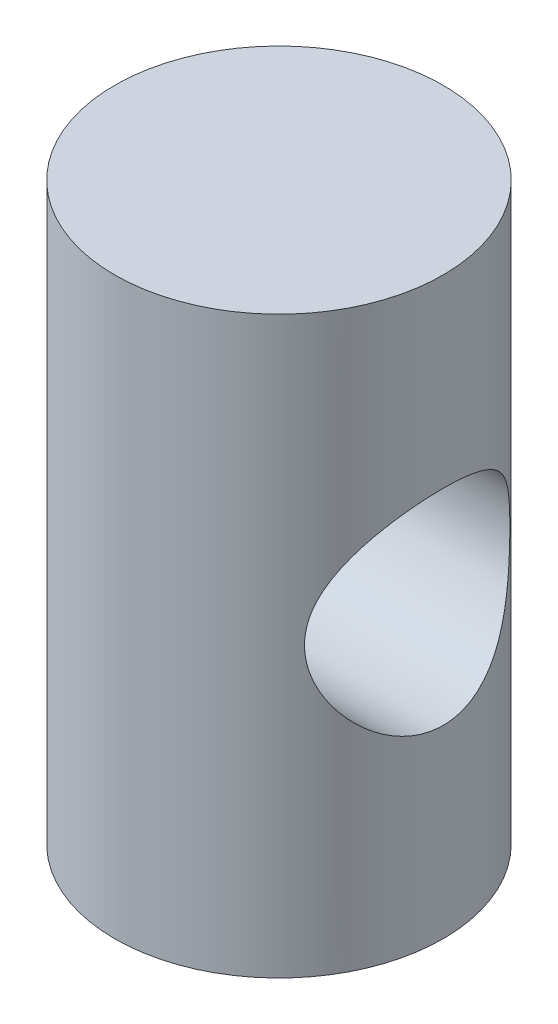
SolidWorks part; units mm, degrees
material "1023 Carbon Steel Sheet (SS)"
ref_plane "Front Plane" through (0, 0, 0) normal (0, 0, 1) x (1, 0, 0)
ref_plane "Top Plane" through (0, 0, 0) normal (0, 1, 0) x (1, 0, 0)
ref_plane "Right Plane" through (0, 0, 0) normal (1, 0, 0) x (0, 0, -1)
sketch "Sketch1" plane through (0, 0, 0) normal (0, 1, 0) x (1, 0, 0)
  circle A0 centre (0, 0) radius 4
  dimension "D1" = 8
extrude "Boss-Extrude1" add sketch "Sketch1" along normal mid plane 14
sketch "Sketch2" plane through (0, 0, 0) normal (1, 0, 0) x (0, 0, -1)
  circle A0 centre (0, 0) radius 2.5
  dimension "D1" = 5
extrude "Cut-Extrude1" cut sketch "Sketch2" against normal mid plane 14
